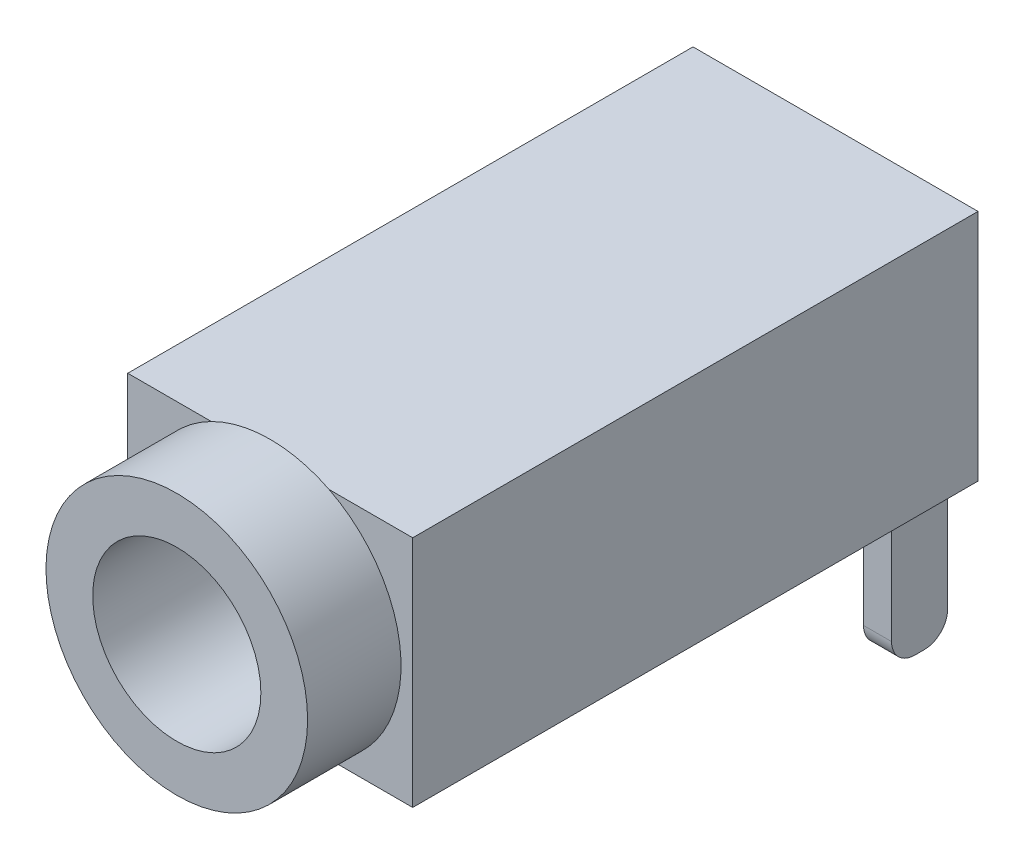
SolidWorks part; units mm, degrees
ref_plane "Front Plane" through (0, 0, 0) normal (0, 0, 1) x (1, 0, 0)
ref_plane "Top Plane" through (0, 0, 0) normal (0, 1, 0) x (1, 0, 0)
ref_plane "Right Plane" through (0, 0, 0) normal (1, 0, 0) x (0, 0, -1)
sketch "Sketch1" plane through (0, 0, 0) normal (0, 0, 1) x (1, 0, 0)
  line L1 (-3.05, -2.5) -> (3.05, -2.5)
  line L2 (-3.05, -2.5) -> (-3.05, 2.5)
  line L3 (-3.05, 2.5) -> (3.05, 2.5)
  line L4 (3.05, -2.5) -> (3.05, 2.5)
  line L5 (-3.05, -2.5) -> (3.05, 2.5) construction
  line L6 (-3.05, 2.5) -> (3.05, -2.5) construction
  point P0 (0, 0)
  dimension "D1" = 5
  dimension "D2" = 6.1
extrude "Boss-Extrude1" add sketch "Sketch1" along normal blind 12.1
sketch "Sketch2" plane through (0, 0, 12.1) normal (0, 0, 1) x (1, 0, 0)
  circle A0 centre (0, 0) radius 2.8
  dimension "D1" = 5.6
extrude "Boss-Extrude2" add sketch "Sketch2" along normal blind 2
sketch "Sketch3" plane through (0, 0, 14.1) normal (0, 0, 1) x (1, 0, 0)
  circle A0 centre (0, 0) radius 1.8
  dimension "D1" = 3.6
extrude "Cut-Extrude1" cut sketch "Sketch3" against normal blind 10
sketch "Sketch4" plane through (0, -2.5, 0) normal (0, -1, 0) x (1, 0, 0)
  line L0 (0, 12.1) -> (0, 0) construction
  line L1 (-1.261, 12.1) -> (1.261, 12.1) construction
  line L3 (-1.261, 12.1) -> (1.261, 12.1) construction
  circle A0 centre (0, 10.5) radius 0.75
  circle A1 centre (0, 3.5) radius 0.75
  dimension "D1" = 1.5
  dimension "D2" = 1.5
  dimension "D3" = 1.6
  dimension "D4" = 7
extrude "Boss-Extrude3" add sketch "Sketch4" along normal blind 0.8
sketch "Sketch5" plane through (0, -2.5, 0) normal (0, -1, 0) x (1, 0, 0)
  line L0 (1.261, 12.1) -> (3.05, 12.1) construction
  line L1 (2, 8.3) -> (2.6, 8.3)
  line L2 (2, 8.3) -> (2, 9.5)
  line L3 (2, 9.5) -> (2.6, 9.5)
  line L4 (2.6, 8.3) -> (2.6, 9.5)
  line L5 (2, 8.3) -> (2.6, 9.5) construction
  line L6 (2, 9.5) -> (2.6, 8.3) construction
  line L7 (2, 5.3) -> (2.6, 5.3)
  line L8 (2, 5.3) -> (2, 6.5)
  line L9 (2, 6.5) -> (2.6, 6.5)
  line L10 (2.6, 5.3) -> (2.6, 6.5)
  line L11 (2, 5.3) -> (2.6, 6.5) construction
  line L12 (2, 6.5) -> (2.6, 5.3) construction
  line L13 (2, 1.3) -> (2.6, 1.3)
  line L14 (2, 1.3) -> (2, 2.5)
  line L15 (2, 2.5) -> (2.6, 2.5)
  line L16 (2.6, 1.3) -> (2.6, 2.5)
  line L17 (2, 1.3) -> (2.6, 2.5) construction
  line L18 (2, 2.5) -> (2.6, 1.3) construction
  line L19 (-2.6, 0.2) -> (-2, 0.2)
  line L20 (-2.6, 0.2) -> (-2.6, 1.4)
  line L21 (-2.6, 1.4) -> (-2, 1.4)
  line L22 (-2, 0.2) -> (-2, 1.4)
  line L23 (-2.6, 0.2) -> (-2, 1.4) construction
  line L24 (-2.6, 1.4) -> (-2, 0.2) construction
  line L25 (-3.05, 12.1) -> (-1.261, 12.1) construction
  line L26 (-3.05, 6.05) -> (3.05, 6.05) construction
  line L27 (-3.05, 12.1) -> (-3.05, 0) construction
  line L28 (3.05, 12.1) -> (3.05, 0) construction
  line L29 (2.3, 8.9) -> (2.3, 5.9) construction
  line L30 (2.3, 5.9) -> (2.3, 1.9) construction
  line L31 (0, 6.05) -> (0, 0) construction
  line L32 (2.3, 1.9) -> (3.05, 1.9) construction
  line L33 (-2.3, 0.8) -> (-3.05, 0.8) construction
  line L34 (-3.05, 0) -> (3.05, 0) construction
  line L35 (2.3, 0.8) -> (3.05, 0.8) construction
  line L36 (-2.3, 1.9) -> (-3.05, 1.9) construction
  line L37 (-2.3, 5.9) -> (-2.3, 1.9) construction
  line L38 (-2.3, 8.9) -> (-2.3, 5.9) construction
  line L39 (2.6, 1.4) -> (2, 0.2) construction
  line L40 (2.6, 0.2) -> (2, 1.4) construction
  line L41 (-2, 2.5) -> (-2.6, 1.3) construction
  line L42 (-2, 1.3) -> (-2.6, 2.5) construction
  line L43 (-2, 6.5) -> (-2.6, 5.3) construction
  line L44 (-2, 5.3) -> (-2.6, 6.5) construction
  line L45 (-2, 9.5) -> (-2.6, 8.3) construction
  line L46 (-2, 8.3) -> (-2.6, 9.5) construction
  line L47 (2, 0.2) -> (2, 1.4)
  line L48 (2.6, 1.4) -> (2, 1.4)
  line L49 (2.6, 0.2) -> (2.6, 1.4)
  line L50 (2.6, 0.2) -> (2, 0.2)
  line L51 (-2.6, 1.3) -> (-2.6, 2.5)
  line L52 (-2, 2.5) -> (-2.6, 2.5)
  line L53 (-2, 1.3) -> (-2, 2.5)
  line L54 (-2, 1.3) -> (-2.6, 1.3)
  line L55 (-2.6, 5.3) -> (-2.6, 6.5)
  line L56 (-2, 6.5) -> (-2.6, 6.5)
  line L57 (-2, 5.3) -> (-2, 6.5)
  line L58 (-2, 5.3) -> (-2.6, 5.3)
  line L59 (-2.6, 8.3) -> (-2.6, 9.5)
  line L60 (-2, 9.5) -> (-2.6, 9.5)
  line L61 (-2, 8.3) -> (-2, 9.5)
  line L62 (-2, 8.3) -> (-2.6, 8.3)
  point P0 (2.3, 8.9)
  point P5 (2.3, 5.9)
  point P10 (2.3, 1.9)
  point P15 (-2.3, 0.8)
  dimension "D1" = 1.2
  dimension "D2" = 0.6
  dimension "D3" = 3.2
  dimension "D4" = 3
  dimension "D5" = 4
  dimension "D6" = 11.3
  dimension "D7" = 4.6
extrude "Boss-Extrude4" add sketch "Sketch5" along normal blind 3 contours L21 L53 L52 L51 | L54 L22 L21 L20 | L58 L57 L56 L55 | L50 L49 L13 L47 | L16 L48 L14 L13 | L61 L60 L59 L62
fillet "Fillet1" radius 0.5 8 edges at (2.3, -5.5, 0.2) (2.3, -5.5, 1.4) (-2.3, -5.5, 1.3) (-2.3, -5.5, 2.5) (-2.3, -5.5, 5.3) (-2.3, -5.5, 6.5) (-2.3, -5.5, 8.3) (-2.3, -5.5, 9.5)
fillet "Fillet2" radius 0.1 2 edges at (0, -3.3, 9.75) (0, -3.3, 2.75)
